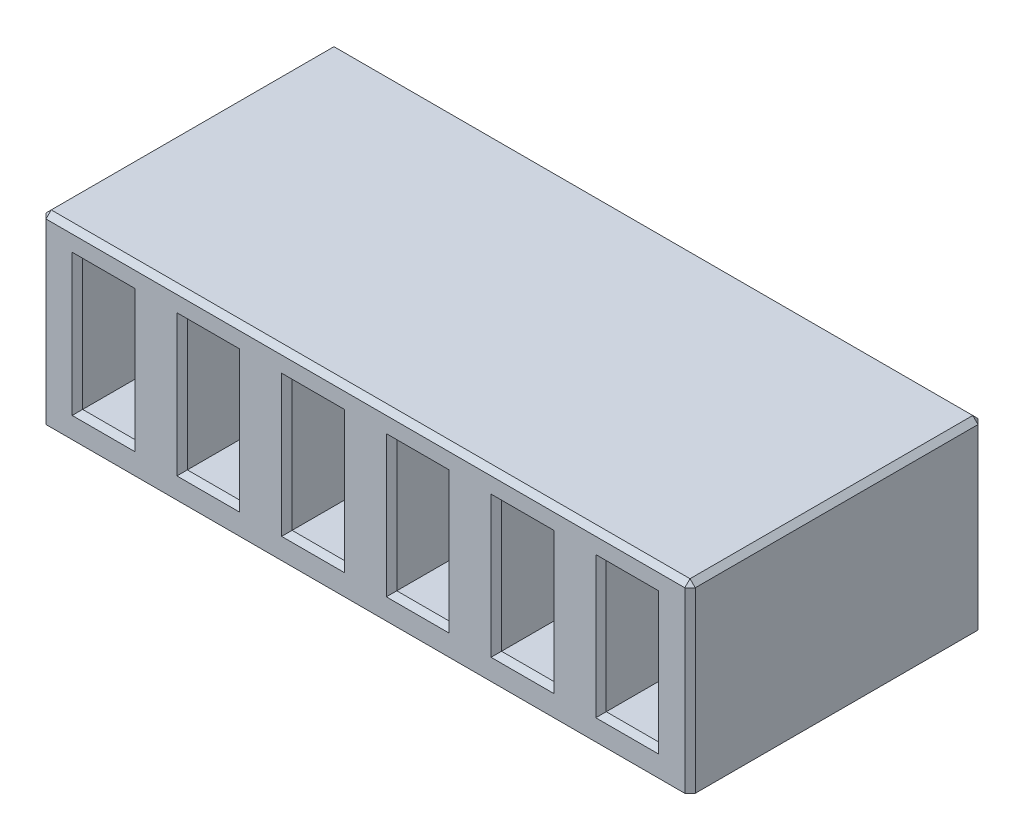
SolidWorks part; units mm, degrees
material "ABS"
ref_plane "Front Plane" through (0, 0, 0) normal (0, 0, 1) x (1, 0, 0)
ref_plane "Top Plane" through (0, 0, 0) normal (0, 1, 0) x (1, 0, 0)
ref_plane "Right Plane" through (0, 0, 0) normal (1, 0, 0) x (0, 0, -1)
sketch "Sketch1" plane through (0, 0, 0) normal (0, 1, 0) x (1, 0, 0)
  line L1 (-6.2, 2.8) -> (6.2, 2.8)
  line L2 (-6.2, 2.8) -> (-6.2, -2.8)
  line L3 (-6.2, -2.8) -> (6.2, -2.8)
  line L4 (6.2, 2.8) -> (6.2, -2.8)
  line L5 (-6.2, 2.8) -> (6.2, -2.8) construction
  line L6 (-6.2, -2.8) -> (6.2, 2.8) construction
  point P0 (0, 0)
  dimension "D1" = 12.4
  dimension "D2" = 5.6
extrude "Boss-Extrude1" add sketch "Sketch1" along normal blind 3.5 contours L3 L4 L1 L2
sketch "Sketch2" plane through (0, 0, 2.8) normal (0, 0, 1) x (1, 0, 0)
  line L0 (-6.2, 1.75) -> (6.2, 1.75) construction
  line L1 (-5.5, 3) -> (-4.5, 3)
  line L2 (-5.5, 3) -> (-5.5, 0.5)
  line L3 (-5.5, 0.5) -> (-4.5, 0.5)
  line L4 (-4.5, 3) -> (-4.5, 0.5)
  line L5 (-5.5, 3) -> (-4.5, 0.5) construction
  line L6 (-5.5, 0.5) -> (-4.5, 3) construction
  line L7 (-6.2, 3.5) -> (-6.2, 0) construction
  line L8 (6.2, 3.5) -> (6.2, 0) construction
  point P0 (-5, 1.75)
  dimension "D1" = 1
  dimension "D2" = 2.5
  dimension "D3" = 0.7
extrude "Cut-Extrude1" cut sketch "Sketch2" against normal blind 4 contours L2 L3 L4 L1
chamfer "Chamfer1" distance 0.1 angle 45 4 edges at (-5, 0.5, 2.8) (-4.5, 1.75, 2.8) (-5, 3, 2.8) (-5.5, 1.75, 2.8)
sketch "Sketch3" plane through (0, 0, -1.2) normal (0, 0, 1) x (1, 0, 0)
  line L0 (-5, 3) -> (-5, 0.5) construction
  line L1 (-5.25, 2.5) -> (-4.75, 2.5)
  line L2 (-5.25, 2.5) -> (-5.25, 2)
  line L3 (-5.25, 2) -> (-4.75, 2)
  line L4 (-4.75, 2.5) -> (-4.75, 2)
  line L5 (-5.25, 2.5) -> (-4.75, 2) construction
  line L6 (-5.25, 2) -> (-4.75, 2.5) construction
  line L7 (-4.5, 3) -> (-5.5, 3) construction
  line L8 (-5.5, 0.5) -> (-4.5, 0.5) construction
  line L9 (-5.5, 3) -> (-4.5, 3) construction
  point P0 (-5, 2.25)
  dimension "D1" = 0.5
  dimension "D2" = 0.5
extrude "Cut-Extrude2" cut sketch "Sketch3" against normal up to next contours L3 L4 L1 L2
chamfer "Chamfer3" distance 0.05 angle 45 4 edges at (-5.25, 2.25, -2.8) (-5, 2.5, -2.8) (-4.75, 2.25, -2.8) (-5, 2, -2.8)
pattern_linear "LPattern1" count 6 spacing 2 along (1, 0, 0) of "Cut-Extrude1", "Chamfer1", "Cut-Extrude2", "Chamfer3"
chamfer "Chamfer2" distance 0.1 angle 45 8 edges at (6.2, 1.75, -2.8) (6.2, 1.75, 2.8) (0, 3.5, 2.8) (-6.2, 1.75, 2.8) (6.2, 3.5, 0) (-6.2, 1.75, -2.8) (-6.2, 3.5, 0) (0, 3.5, -2.8)
